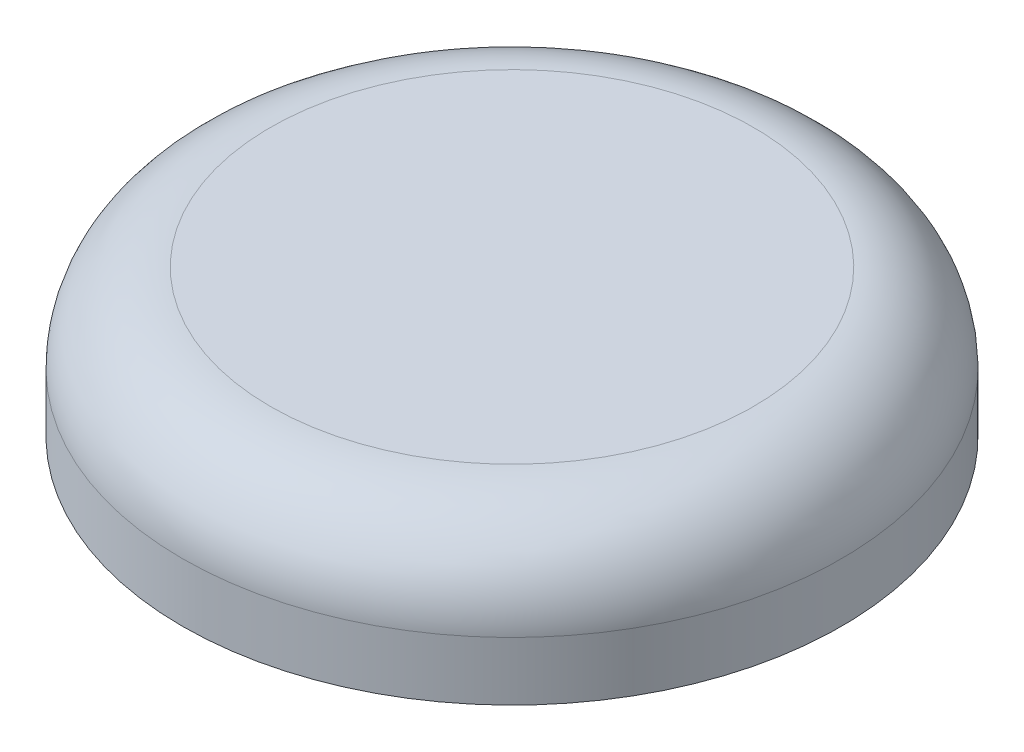
SolidWorks part; units mm, degrees
ref_plane "Front Plane" through (0, 0, 0) normal (0, 0, 1) x (1, 0, 0)
ref_plane "Top Plane" through (0, 0, 0) normal (0, 1, 0) x (1, 0, 0)
ref_plane "Right Plane" through (0, 0, 0) normal (1, 0, 0) x (0, 0, -1)
sketch "Sketch1" plane through (0, 0, 0) normal (0, 1, 0) x (1, 0, 0)
  circle A0 centre (0, 0) radius 11.25
  dimension "D1" = 22.5
extrude "Boss-Extrude1" add sketch "Sketch1" along normal blind 5
fillet "Fillet1" radius 3 1 edges at (0, 5, 11.25)
